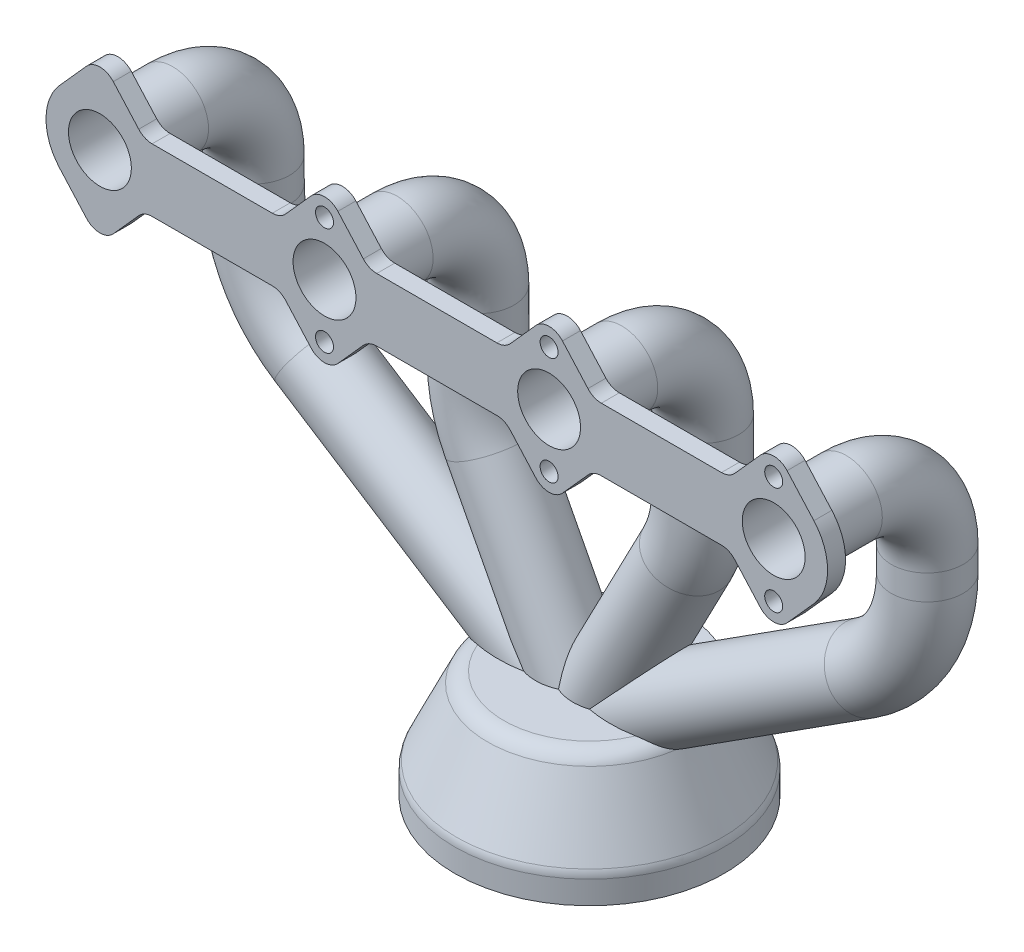
SolidWorks part; units mm, degrees
ref_plane "Front Plane" through (0, 0, 0) normal (0, 0, 1) x (1, 0, 0)
ref_plane "Top Plane" through (0, 0, 0) normal (0, 1, 0) x (1, 0, 0)
ref_plane "Right Plane" through (0, 0, 0) normal (1, 0, 0) x (0, 0, -1)
sketch "Sketch1" plane through (0, 0, 0) normal (0, 0, 1) x (1, 0, 0)
  line L0 (0, 0) -> (-41663.6738, 0) construction
  line L1 (0, 0) -> (0, 41663.6738) construction
  line L2 (-75, 0) -> (-75, 15)
  line L3 (-75, 15) -> (-54.0162, 60)
  line L4 (-54.0162, 60) -> (0, 60)
  line L5 (0, 60) -> (0, 0)
  line L6 (0, 0) -> (-75, 0)
  dimension "D1" = 75
  dimension "D2" = 15
  dimension "D3" = 155
  dimension "D4" = 60
revolve "Revolve1" add sketch "Sketch1" angle 360 about L1
ref_plane "Plane1" through (0, 0, 85) normal (0, 0, 1) x (1, 0, 0)
sketch "Sketch2" plane through (0, 0, 85) normal (0, 0, 1) x (1, 0, 0)
  line L0 (0, 0) -> (0, 50000) construction
  line L1 (-156.4398, 260) -> (49843.5602, 260) construction
  line L2 (-194.9536, 296.6667) -> (-209.8607, 280)
  line L3 (-165.1393, 280) -> (-180.0464, 296.6667)
  line L4 (-165.1393, 240) -> (-180.0464, 223.3333)
  line L5 (-194.9536, 223.3333) -> (-209.8607, 240)
  line L6 (-69.9536, 296.6667) -> (-84.8607, 280)
  line L7 (-40.1393, 280) -> (-55.0464, 296.6667)
  line L8 (-40.1393, 240) -> (-55.0464, 223.3333)
  line L9 (-69.9536, 223.3333) -> (-84.8607, 240)
  line L10 (55.0464, 296.6667) -> (40.1393, 280)
  line L11 (84.8607, 280) -> (69.9536, 296.6667)
  line L12 (84.8607, 240) -> (69.9536, 223.3333)
  line L13 (55.0464, 223.3333) -> (40.1393, 240)
  line L14 (180.0464, 296.6667) -> (165.1393, 280)
  line L15 (209.8607, 280) -> (194.9536, 296.6667)
  line L16 (209.8607, 240) -> (194.9536, 223.3333)
  line L17 (180.0464, 223.3333) -> (165.1393, 240)
  line L19 (-187.5, 277.5) -> (187.5, 277.5)
  line L20 (-187.5, 277.5) -> (-187.5, 242.5)
  line L21 (-187.5, 242.5) -> (187.5, 242.5)
  line L22 (187.5, 277.5) -> (187.5, 242.5)
  arc A0 (-209.8607, 280) -> (-209.8607, 240) centre (-187.5, 260) ccw
  circle A1 centre (-187.5, 290) radius 5
  arc A2 (-180.0464, 296.6667) -> (-194.9536, 296.6667) centre (-187.5, 290) ccw
  arc A3 (-84.8607, 280) -> (-84.8607, 240) centre (-62.5, 260) ccw
  arc A4 (-180.0464, 223.3333) -> (-194.9536, 223.3333) centre (-187.5, 230) cw
  circle A5 centre (-187.5, 230) radius 5
  circle A6 centre (-62.5, 290) radius 5
  arc A7 (-165.1393, 240) -> (-165.1393, 280) centre (-187.5, 260) ccw
  arc A8 (-55.0464, 296.6667) -> (-69.9536, 296.6667) centre (-62.5, 290) ccw
  arc A9 (-55.0464, 223.3333) -> (-69.9536, 223.3333) centre (-62.5, 230) cw
  circle A10 centre (-62.5, 230) radius 5
  arc A11 (-40.1393, 240) -> (-40.1393, 280) centre (-62.5, 260) ccw
  arc A12 (40.1393, 280) -> (40.1393, 240) centre (62.5, 260) ccw
  circle A13 centre (62.5, 290) radius 5
  arc A14 (69.9536, 296.6667) -> (55.0464, 296.6667) centre (62.5, 290) ccw
  arc A15 (69.9536, 223.3333) -> (55.0464, 223.3333) centre (62.5, 230) cw
  circle A16 centre (62.5, 230) radius 5
  arc A17 (84.8607, 240) -> (84.8607, 280) centre (62.5, 260) ccw
  arc A18 (165.1393, 280) -> (165.1393, 240) centre (187.5, 260) ccw
  circle A19 centre (187.5, 290) radius 5
  arc A20 (194.9536, 296.6667) -> (180.0464, 296.6667) centre (187.5, 290) ccw
  arc A21 (194.9536, 223.3333) -> (180.0464, 223.3333) centre (187.5, 230) cw
  circle A22 centre (187.5, 230) radius 5
  arc A23 (209.8607, 240) -> (209.8607, 280) centre (187.5, 260) ccw
  point P61 (-187.5, 260)
  point P62 (187.5, 260)
  dimension "D2" = 60
  dimension "D3" = 10
  dimension "D4" = 20
  dimension "D1" = 260
  dimension "D5" = 187.5
  dimension "D6" = 4
  dimension "D7" = 125
  dimension "D8" = 35
extrude "Boss-Extrude1" add sketch "Sketch2" against normal blind 10 separate body contours L16 A23 L15 A20 L14 A18 L19 L22 L21 L17 A21 A22 A19 | L19 A18 L21 L22 | A18 L19 A17 L21 | L21 A17 L19 A12 | L12 A17 L21 A12 L13 A15 A16 | L19 A17 L11 A14 L10 A12 A13 | A12 L19 A11 L21 | L21 A11 L19 A3 | L19 A11 L7 A8 L6 A3 A6 | L8 A11 L21 A3 L9 A9 A10 | A7 L21 A3 L19 | L21 A7 L19 L20
sketch "Sketch3" plane through (0, 0, 0) normal (1, 0, 0) x (0, 0, -1)
  line L0 (-85, 260) -> (-44.5481, 260)
  line L1 (-85, 165) -> (-85, -165) construction
  line L2 (0.4519, 215) -> (0.4519, 40)
  arc A0 (-44.5481, 260) -> (0.4519, 215) centre (-44.5481, 215) cw
  point P8 (0, 0)
  dimension "D2" = 45
  dimension "D1" = 40
sketch "Sketch4" plane through (0, 0, 85) normal (0, 0, 1) x (1, 0, 0)
  line L0 (187.5, 260) -> (187.5, 201.0449)
  line L1 (152.929, 137.8746) -> (0, 40)
  line L2 (62.5, 260) -> (62.5, 178.3607)
  line L3 (54.0186, 143.7156) -> (0, 40)
  line L4 (0, 215) -> (0, 40) construction
  arc A0 (187.5, 201.0449) -> (152.929, 137.8746) centre (112.5, 201.0449) cw
  arc A1 (69.9536, 296.6667) -> (55.0464, 296.6667) centre (62.5, 290) ccw construction
  arc A2 (62.5, 178.3607) -> (54.0186, 143.7156) centre (-12.5, 178.3607) cw
  point P3 (0, 0)
  point P9 (187.5, 160)
  point P14 (62.5, 300)
  point P17 (62.5, 160)
  point P20 (0, 40)
  point P21 (0, 40)
  point P22 (0, 0)
  point P23 (0, 0)
  dimension "D1" = 75
  dimension "D3" = 75
  dimension " 100" = 100
  dimension "D2" = 100
curve "Curve1"
sweep "Sweep1" add path "Curve1" circular profile diameter 40 parameters "D3"=40
mirror "Mirror1" about plane through (0, 0, 0) normal (1, 0, 0) of "Sweep1"
sketch "Sketch19" plane through (0, 0, 0) normal (0, 0, 1) x (1, 0, 0)
  line L0 (-63.9662, 0) -> (-63.9662, 15)
  line L1 (-75, 0) -> (75, 0) construction
  line L2 (75, 15) -> (-75, 15) construction
  line L3 (-63.9662, 15) -> (-47.6455, 50)
  line L4 (-47.6455, 50) -> (0, 50)
  line L5 (0, 50) -> (0, 0)
  line L6 (0, 0) -> (-63.9662, 0)
  line L7 (-57.309, 52.9386) -> (-75, 15) construction
  line L8 (-75, 15) -> (-75, 0) construction
  line L9 (51.4955, 60) -> (-51.4955, 60) construction
  line L10 (-18.2922, 60) -> (-51.4955, 60) construction
  line L11 (0, 0) -> (0, 196.8672) construction
  dimension "D1" = 10
  dimension "D2" = 10
revolve "Cut-Revolve3" cut sketch "Sketch19" angle 360 about L11
sweep "Cut-Sweep1" cut path "Curve1" circular profile diameter 35 parameters "D3"=35
mirror "Mirror2" about plane through (0, 0, 0) normal (1, 0, 0) of "Cut-Sweep1"
fillet "Fillet1" radius 10 6 edges at (163.133, 277.5, 80) (86.867, 277.5, 80) (-38.133, 277.5, 80) (38.133, 277.5, 80) (-86.867, 277.5, 80) (-163.133, 277.5, 80)
fillet "Fillet2" radius 10 6 edges at (-86.867, 242.5, 80) (-163.133, 242.5, 80) (-38.133, 242.5, 80) (38.133, 242.5, 80) (86.867, 242.5, 80) (163.133, 242.5, 80)
fillet "Fillet4" radius 10 2 edges at (0, 15, -75) (0, 60, 54.0162)
